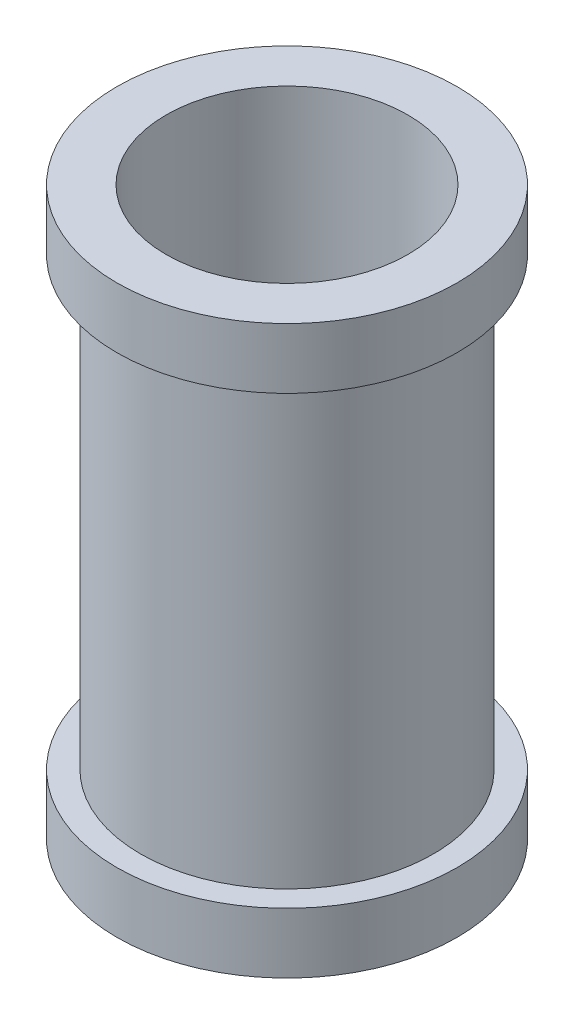
SolidWorks part; units mm, degrees
ref_plane "Front Plane" through (0, 0, 0) normal (0, 0, 1) x (1, 0, 0)
ref_plane "Top Plane" through (0, 0, 0) normal (0, 1, 0) x (1, 0, 0)
ref_plane "Right Plane" through (0, 0, 0) normal (1, 0, 0) x (0, 0, -1)
sketch "Sketch3" plane through (0, 0, 0) normal (0, 0, 1) x (1, 0, 0)
  line L0 (0, 0) -> (8.255, 0)
  line L1 (8.255, 0) -> (8.255, 10.16)
  line L2 (8.255, 10.16) -> (4.2862, 10.16)
  line L3 (4.2862, 10.16) -> (4.2862, 85.09)
  line L4 (8.255, 85.09) -> (4.2862, 85.09)
  line L5 (8.255, 85.09) -> (8.255, 95.25)
  line L6 (8.255, 95.25) -> (0, 95.25)
  line L7 (0, 95.25) -> (0, 0)
  line L9 (-20.32, 95.25) -> (-20.32, 0) construction
  dimension "D1" = 8.255
revolve "Revolve1" add sketch "Sketch3" angle 360 about L9
sketch "Sketch5" plane through (0, 0, 0) normal (0, -1, 0) x (1, 0, 0)
  line L0 (-48.895, 0) -> (8.255, 0) construction
  circle A0 centre (-20.32, 0) radius 28.575 construction
  point P5 (-20.32, 0)
sketch3d "3DSketch2"
  circle A0 centre (-20.32, 47.625, 0) radius 24.6062 construction
  point P3 (-20.32, 72.2313, 0)
  point P9 (-20.32, 47.625, 0)
  dimension "D1" = 49.2125
